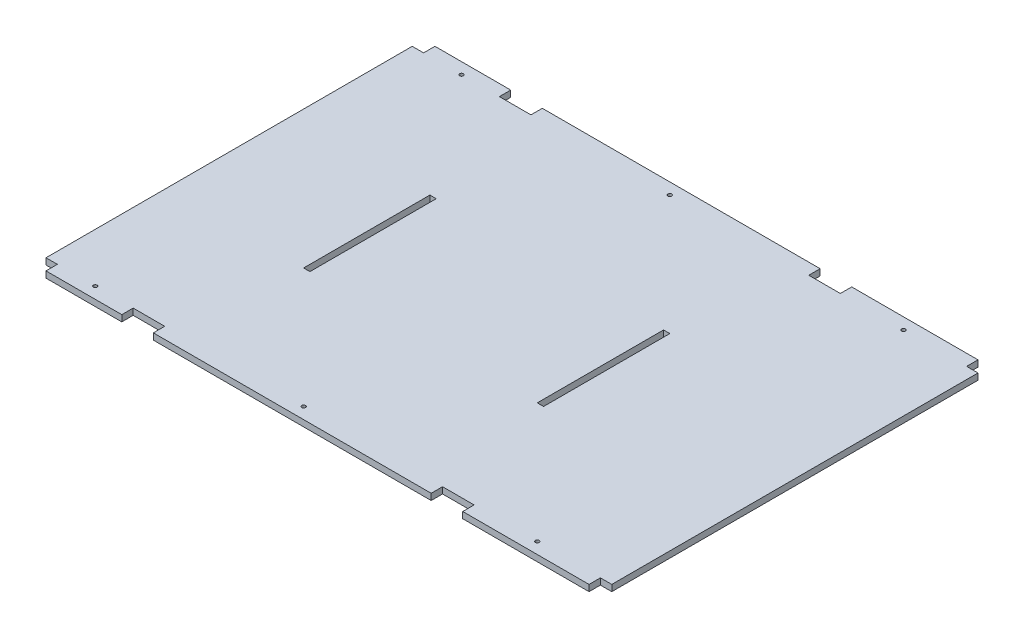
SolidWorks part; units mm, degrees
material "Perspex (TM) GS Acrylic Cast Sheet"
ref_plane "Ebene vorne" through (0, 0, 0) normal (0, 0, 1) x (1, 0, 0)
ref_plane "Ebene oben" through (0, 0, 0) normal (0, 1, 0) x (1, 0, 0)
ref_plane "Ebene rechts" through (0, 0, 0) normal (1, 0, 0) x (0, 0, -1)
sketch "Skizze1" plane through (0, 0, 0) normal (0, 1, 0) x (1, 0, 0)
  line L1 (0, 0) -> (450, 0)
  line L2 (0, 0) -> (0, -310)
  line L3 (0, -310) -> (450, -310)
  line L4 (450, 0) -> (450, -310)
  line L5 (0, 0) -> (450, -310) construction
  line L6 (0, -310) -> (450, 0) construction
  point P4 (225, -155)
  dimension "D1" = 450
  dimension "D2" = 310
extrude "Aufsatz-Linear austragen1" add sketch "Skizze1" along normal blind 5
sketch "Skizze2" plane through (0, 5, 0) normal (0, 1, 0) x (1, 0, 0)
  line L0 (450, 0) -> (0, 0) construction
  line L1 (0, 0) -> (10, 0)
  line L2 (0, 0) -> (0, -10)
  line L3 (0, -10) -> (10, -10)
  line L4 (10, 0) -> (10, -10)
  line L5 (0, 0) -> (10, -10) construction
  line L6 (0, -10) -> (10, 0) construction
  line L7 (10, -10) -> (440, -10) construction
  line L8 (10, -10) -> (10, -300) construction
  line L9 (10, -300) -> (440, -300) construction
  line L10 (440, -10) -> (440, -300) construction
  line L11 (10, -10) -> (440, -300) construction
  line L12 (10, -300) -> (440, -10) construction
  line L13 (440, -300) -> (450, -300)
  line L14 (440, -300) -> (440, -310)
  line L15 (440, -310) -> (450, -310)
  line L16 (450, -300) -> (450, -310)
  line L17 (440, -300) -> (450, -310) construction
  line L18 (440, -310) -> (450, -300) construction
  line L19 (440, -10) -> (450, -10)
  line L20 (440, -10) -> (440, 0)
  line L21 (440, 0) -> (450, 0)
  line L22 (450, -10) -> (450, 0)
  line L23 (440, -10) -> (450, 0) construction
  line L24 (440, 0) -> (450, -10) construction
  line L25 (10, -300) -> (0, -300)
  line L26 (10, -300) -> (10, -310)
  line L27 (10, -310) -> (0, -310)
  line L28 (0, -300) -> (0, -310)
  line L29 (10, -300) -> (0, -310) construction
  line L30 (10, -310) -> (0, -300) construction
  line L31 (70, -10) -> (95, -10)
  line L32 (70, -10) -> (70, 0)
  line L33 (70, 0) -> (95, 0)
  line L34 (95, -10) -> (95, 0)
  line L35 (70, -10) -> (95, 0) construction
  line L36 (70, 0) -> (95, -10) construction
  line L37 (0, -310) -> (450, -310) construction
  line L38 (315, 0) -> (340, 0)
  line L39 (315, 0) -> (315, -10)
  line L40 (315, -10) -> (340, -10)
  line L41 (340, 0) -> (340, -10)
  line L42 (315, 0) -> (340, -10) construction
  line L43 (315, -10) -> (340, 0) construction
  line L44 (340, -300) -> (315, -300)
  line L45 (340, -300) -> (340, -310)
  line L46 (340, -310) -> (315, -310)
  line L47 (315, -300) -> (315, -310)
  line L48 (340, -300) -> (315, -310) construction
  line L49 (340, -310) -> (315, -300) construction
  line L51 (70, -300) -> (95, -300)
  line L52 (70, -300) -> (70, -310)
  line L53 (70, -310) -> (95, -310)
  line L54 (95, -300) -> (95, -310)
  line L55 (70, -300) -> (95, -310) construction
  line L56 (70, -310) -> (95, -300) construction
  point P4 (5, -5)
  point P9 (225, -155)
  point P13 (445, -305)
  point P18 (445, -5)
  point P23 (5, -305)
  point P29 (82.5, -5)
  point P36 (327.5, -5)
  point P41 (327.5, -305)
  point P48 (82.5, -305)
  dimension "D1" = 25
  dimension "D2" = 25
  dimension "D3" = 25
  dimension "D4" = 25
  dimension "D5" = 220
  dimension "D6" = 220
  dimension "D7" = 10
  dimension "D8" = 10
  dimension "D9" = 10
  dimension "D10" = 10
  dimension "D11" = 100
  dimension "D12" = 100
extrude "Schnitt-Linear austragen1" cut sketch "Skizze2" against normal through all
sketch "Skizze3" plane through (0, 5, 0) normal (0, 1, 0) x (1, 0, 0)
  line L0 (0, -155) -> (450, -155) construction
  line L3 (0, -10) -> (0, -300) construction
  line L6 (450, -300) -> (450, -10) construction
  line L7 (110, -105) -> (115, -105)
  line L8 (110, -105) -> (110, -205)
  line L9 (110, -205) -> (115, -205)
  line L10 (115, -105) -> (115, -205)
  line L11 (110, -105) -> (115, -205) construction
  line L12 (110, -205) -> (115, -105) construction
  line L13 (295, -105) -> (300, -105)
  line L14 (295, -105) -> (295, -205)
  line L15 (295, -205) -> (300, -205)
  line L16 (300, -105) -> (300, -205)
  line L17 (295, -105) -> (300, -205) construction
  line L18 (295, -205) -> (300, -105) construction
  line L19 (95, -10) -> (95, 0) construction
  line L20 (315, 0) -> (315, -10) construction
  point P6 (112.5, -155)
  point P12 (112.5, -155)
  point P17 (297.5, -155)
  dimension "D1" = 5
  dimension "D2" = 100
  dimension "D3" = 15
  dimension "D4" = 15
extrude "Schnitt-Linear austragen2" cut sketch "Skizze3" against normal through all
sketch "Skizze4" plane through (0, 5, 0) normal (0, 1, 0) x (1, 0, 0)
  line L1 (10, -10) -> (70, -10) construction
  line L2 (10, -10) -> (10, -300) construction
  line L3 (10, -300) -> (70, -300) construction
  line L4 (70, -10) -> (70, -300) construction
  line L5 (10, -10) -> (70, -300) construction
  line L6 (10, -300) -> (70, -10) construction
  line L7 (95, -10) -> (315, -10) construction
  line L8 (95, -10) -> (95, -300) construction
  line L9 (95, -300) -> (315, -300) construction
  line L10 (315, -10) -> (315, -300) construction
  line L11 (95, -10) -> (315, -300) construction
  line L12 (95, -300) -> (315, -10) construction
  line L13 (340, -10) -> (440, -10) construction
  line L14 (340, -10) -> (340, -300) construction
  line L15 (340, -300) -> (440, -300) construction
  line L16 (440, -10) -> (440, -300) construction
  line L17 (340, -10) -> (440, -300) construction
  line L18 (340, -300) -> (440, -10) construction
  circle A0 centre (40, -10) radius 1.5
  circle A1 centre (205, -10) radius 1.5
  circle A2 centre (390, -10) radius 1.5
  circle A3 centre (40, -300) radius 1.5
  circle A4 centre (205, -300) radius 1.5
  circle A5 centre (390, -300) radius 1.5
  point P4 (40, -155)
  point P11 (205, -155)
  point P18 (390, -155)
  dimension "D1" = 3
extrude "Schnitt-Linear austragen3" cut sketch "Skizze4" against normal through all
sketch "Skizze5" plane through (0, 5, 0) normal (0, 1, 0) x (1, 0, 0)
  line L0 (0, -10) -> (0, -300) construction
  line L1 (-1, -300) -> (1, -300)
  line L2 (-1, -300) -> (-1, -10)
  line L3 (-1, -10) -> (1, -10)
  line L4 (1, -300) -> (1, -10)
  line L5 (-1, -300) -> (1, -10) construction
  line L6 (-1, -10) -> (1, -300) construction
  line L7 (0, -10) -> (10, -10) construction
  line L8 (70, 0) -> (10, 0) construction
  line L9 (10, 1) -> (70, 1)
  line L10 (10, 1) -> (10, -1)
  line L11 (10, -1) -> (70, -1)
  line L12 (70, 1) -> (70, -1)
  line L13 (10, 1) -> (70, -1) construction
  line L14 (10, -1) -> (70, 1) construction
  line L15 (70, 0) -> (70, -10) construction
  line L16 (315, 0) -> (95, 0) construction
  line L17 (95, 1) -> (315, 1)
  line L18 (95, 1) -> (95, -1)
  line L19 (95, -1) -> (315, -1)
  line L20 (315, 1) -> (315, -1)
  line L21 (95, 1) -> (315, -1) construction
  line L22 (95, -1) -> (315, 1) construction
  line L23 (315, 0) -> (315, -10) construction
  line L24 (440, 0) -> (340, 0) construction
  line L25 (440, 1) -> (340, 1)
  line L26 (440, 1) -> (440, -1)
  line L27 (440, -1) -> (340, -1)
  line L28 (340, 1) -> (340, -1)
  line L29 (440, 1) -> (340, -1) construction
  line L30 (440, -1) -> (340, 1) construction
  line L31 (340, -10) -> (340, 0) construction
  line L32 (450, -300) -> (450, -10) construction
  line L33 (451, -10) -> (449, -10)
  line L34 (451, -10) -> (451, -300)
  line L35 (451, -300) -> (449, -300)
  line L36 (449, -10) -> (449, -300)
  line L37 (451, -10) -> (449, -300) construction
  line L38 (451, -300) -> (449, -10) construction
  line L39 (450, -300) -> (440, -300) construction
  line L40 (450, -155) -> (50450, -155) construction
  line L41 (440, -309) -> (340, -311) construction
  line L42 (440, -311) -> (340, -309) construction
  line L43 (95, -309) -> (315, -311) construction
  line L44 (95, -311) -> (315, -309) construction
  line L45 (10, -309) -> (70, -311) construction
  line L46 (10, -311) -> (70, -309) construction
  line L47 (340, -311) -> (340, -309)
  line L48 (440, -309) -> (340, -309)
  line L49 (440, -311) -> (440, -309)
  line L50 (440, -311) -> (340, -311)
  line L51 (315, -311) -> (315, -309)
  line L52 (95, -309) -> (315, -309)
  line L53 (95, -311) -> (95, -309)
  line L54 (95, -311) -> (315, -311)
  line L55 (70, -311) -> (70, -309)
  line L56 (10, -309) -> (70, -309)
  line L57 (10, -311) -> (10, -309)
  line L58 (10, -311) -> (70, -311)
  point P0 (0, -155)
  point P9 (40, 0)
  point P18 (205, 0)
  point P27 (390, 0)
  point P36 (450, -155)
  point P59 (390, -310)
  point P60 (205, -310)
  point P61 (40, -310)
  dimension "D1" = 2
extrude "Schnitt-Linear austragen4" cut sketch "Skizze5" against normal through all
